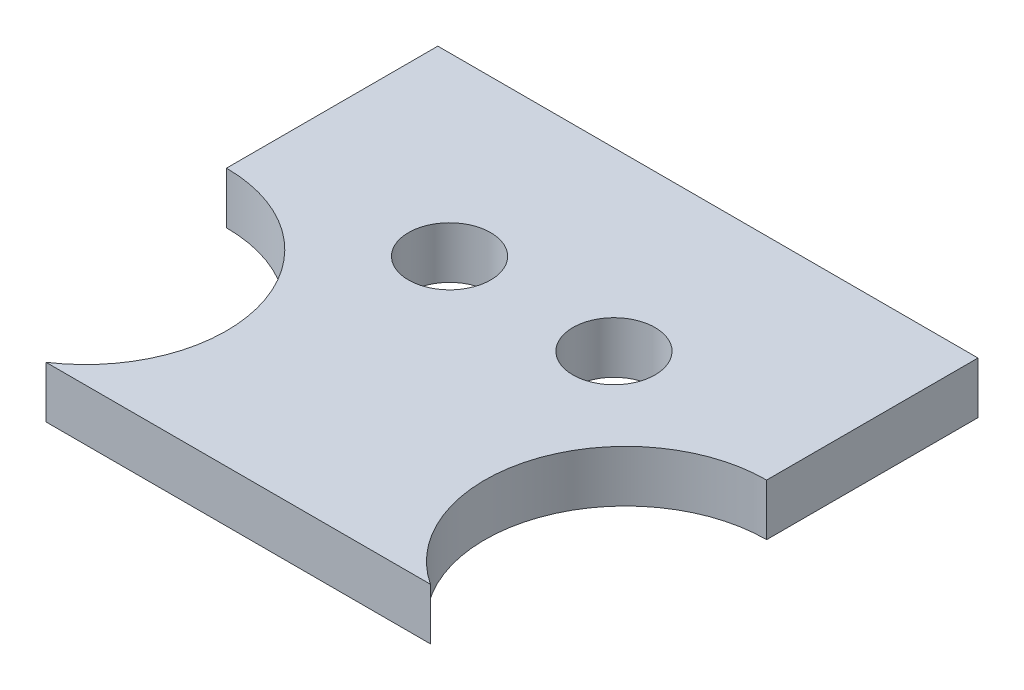
SolidWorks part; units mm, degrees
ref_plane "Спереди" through (0, 0, 0) normal (0, 0, 1) x (1, 0, 0)
ref_plane "Сверху" through (0, 0, 0) normal (0, 1, 0) x (1, 0, 0)
ref_plane "Справа" through (0, 0, 0) normal (1, 0, 0) x (0, 0, -1)
other "Configuration Table"
sketch "Sketch1" plane through (0, 0, 0) normal (0, 1, 0) x (1, 0, 0)
  line L0 (-23, -3) -> (23, -3) construction
  line L1 (-23, 15) -> (23, 15)
  line L2 (-23, 15) -> (-23, -15) construction
  line L3 (-23, -15) -> (23, -15) construction
  line L4 (23, 15) -> (23, -15) construction
  line L5 (0, -15) -> (0, 15) construction
  line L6 (-23, 0) -> (23, 0) construction
  line L7 (-23, -3) -> (-23, 15)
  line L8 (23, 15) -> (23, -3)
  line L9 (11, -15) -> (-11, -15) construction
  line L10 (-23, -15) -> (23, -15) construction
  line L11 (-23, -15) -> (-23, -25) construction
  line L12 (23, -15) -> (23, -25) construction
  line L13 (-23, -25) -> (23, -25) construction
  line L14 (-16.3668, -25) -> (16.3668, -25)
  circle A0 centre (-7, 0) radius 3.5
  circle A1 centre (7, 0) radius 3.5
  arc A2 (-23, -3) -> (-11, -15) centre (-23, -15) cw
  arc A3 (23, -3) -> (11, -15) centre (23, -15) ccw
  arc A4 (-11, -15) -> (-16.3668, -25) centre (-23, -15) cw
  arc A5 (11, -15) -> (16.3668, -25) centre (23, -15) ccw
  point P0 (0, 0)
  point P8 (-23, -3)
  dimension "D3" = 7
  dimension "D1" = 7
  dimension "D2" = 14
  dimension "D4" = 16
  dimension "D5" = 15
  dimension "D6" = 3
  dimension "D7" = 25
extrude "Boss-Extrude1" add sketch "Sketch1" along normal blind 4.4
sketch "Sketch2" plane through (0, 4.4, 0) normal (0, 1, 0) x (1, 0, 0)
  line L0 (-23, 15) -> (-23, -3) construction
  line L1 (-23, -25) -> (23, -25)
  line L2 (-23, -25) -> (-23, 0)
  line L3 (-23, 0) -> (23, 0) construction
  line L4 (23, -25) -> (23, 0)
  line L5 (0, 0) -> (0, -25) construction
  line L6 (-23, -12.5) -> (23, -12.5) construction
  line L7 (23, -3) -> (23, 15) construction
  line L8 (-23, 0) -> (23, 0) construction
  line L9 (-23, 0) -> (-23, 15)
  line L10 (23, 0) -> (23, 15)
  line L11 (-23, 15) -> (23, 15)
  line L12 (23, 15) -> (-23, 15) construction
  circle A0 centre (-7, 0) radius 1.45
  circle A1 centre (7, 0) radius 1.45
  point P176 (0, -12.5)
  dimension "D2" = 2.9
  dimension "D1" = 25
